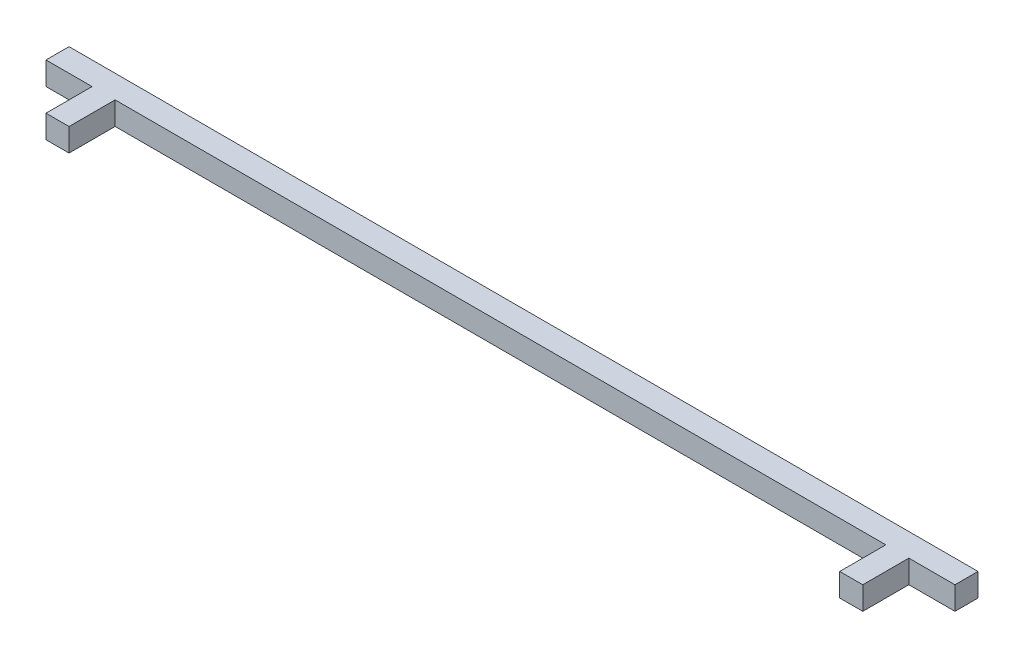
SolidWorks part; units mm, degrees
ref_plane "Front Plane" through (0, 0, 0) normal (0, 0, 1) x (1, 0, 0)
ref_plane "Top Plane" through (0, 0, 0) normal (0, 1, 0) x (1, 0, 0)
ref_plane "Right Plane" through (0, 0, 0) normal (1, 0, 0) x (0, 0, -1)
sketch "Sketch1" plane through (0, 0, 0) normal (0, 1, 0) x (1, 0, 0)
  line L0 (0, 0) -> (0, 3)
  line L1 (0, 3) -> (118.32, 3)
  line L2 (118.32, 3) -> (118.32, 0)
  line L3 (118.32, 0) -> (112.32, 0)
  line L4 (112.32, 0) -> (112.32, -6)
  line L5 (112.32, -6) -> (109.32, -6)
  line L6 (109.32, -6) -> (109.32, 0)
  line L7 (109.32, 0) -> (9, 0)
  line L8 (9, 0) -> (9, -6)
  line L9 (9, -6) -> (6, -6)
  line L10 (6, -6) -> (6, 0)
  line L11 (6, 0) -> (0, 0)
  dimension "D1" = 118.32
  dimension "D2" = 3
  dimension "D3" = 6
  dimension "D4" = 6
  dimension "D5" = 3
  dimension "D6" = 6
  dimension "D7" = 6
  dimension "D8" = 3
extrude "Boss-Extrude2" add sketch "Sketch1" along normal blind 3
